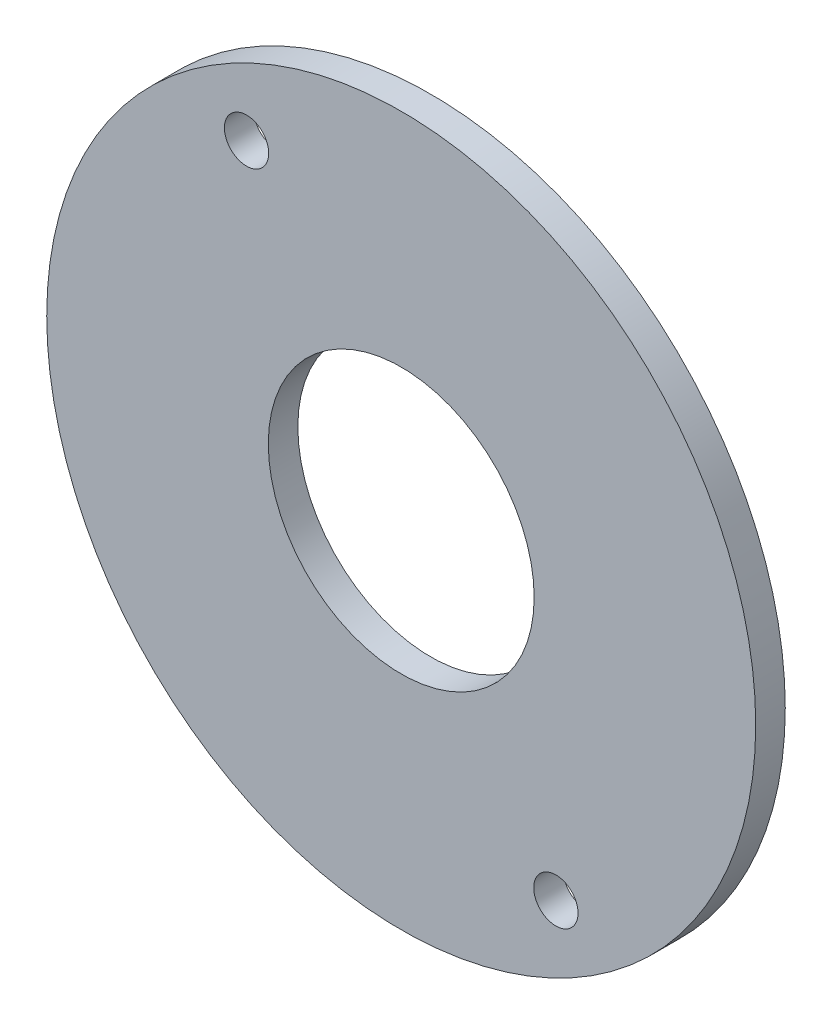
SolidWorks part; units mm, degrees
material "6061-T6 (SS)"
ref_plane "Front Plane" through (0, 0, 0) normal (0, 0, 1) x (1, 0, 0)
ref_plane "Top Plane" through (0, 0, 0) normal (0, 1, 0) x (1, 0, 0)
ref_plane "Right Plane" through (0, 0, 0) normal (1, 0, 0) x (0, 0, -1)
sketch "Sketch1" plane through (0, 0, 0) normal (0, 0, 1) x (1, 0, 0)
  circle A0 centre (136.607, 62.2618) radius 38.1
  circle A1 centre (153.2295, 35.2108) radius 2.3813 construction
  circle A4 centre (136.607, 62.2618) radius 14.2875
  circle A6 centre (153.2295, 35.2108) radius 2.3813
  circle A7 centre (119.9845, 89.3128) radius 2.3812 construction
  circle A8 centre (119.9845, 89.3128) radius 2.3813
extrude "Boss-Extrude1" add sketch "Sketch1" along normal blind 3.175
